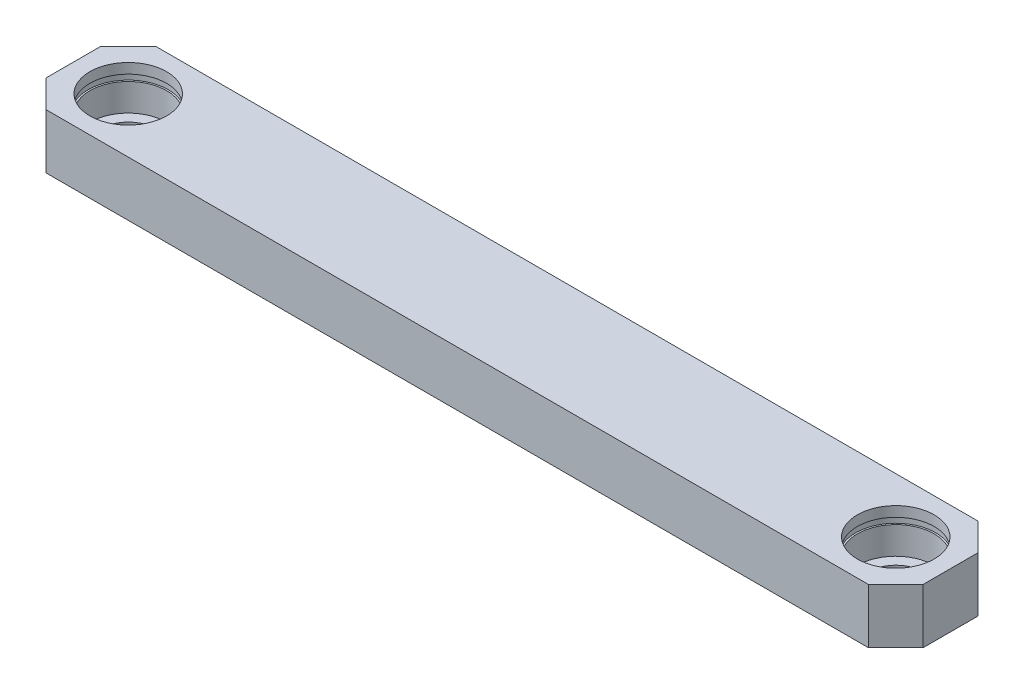
SolidWorks part; units mm, degrees
ref_plane "Front Plane" through (0, 0, 0) normal (0, 0, 1) x (1, 0, 0)
ref_plane "Top Plane" through (0, 0, 0) normal (0, 1, 0) x (1, 0, 0)
ref_plane "Right Plane" through (0, 0, 0) normal (1, 0, 0) x (0, 0, -1)
sketch "Sketch1" plane through (0, 0, 0) normal (0, 1, 0) x (1, 0, 0)
  line L0 (10, 10) -> (10, -10) construction
  line L1 (0, 10) -> (160, 10)
  line L2 (0, 10) -> (0, -10)
  line L3 (0, -10) -> (160, -10)
  line L4 (160, 10) -> (160, -10)
  line L5 (150, 10) -> (150, -10) construction
  dimension "L_s" = 160
  dimension "W" = 20
  dimension "F" = 10
  dimension "L" = 140
  dimension "MSM_11" = 10
extrude "Boss-Extrude1" add sketch "Sketch1" along normal blind 10
chamfer "Chamfer1" distance 5 angle 45 4 edges at (0, 5, -10) (160, 5, -10) (160, 5, 10) (0, 5, 10)
sketch "Sketch2" plane through (0, 0, 0) normal (0, 0, 1) x (1, 0, 0)
  line L0 (2.7, 7) -> (3, 7)
  line L1 (3, 7) -> (3, 2)
  line L2 (2.7, 8.15) -> (2.7, 7)
  line L3 (3, 2) -> (5, 2)
  line L4 (5, 2) -> (5, 0)
  line L5 (7.5, 10) -> (7.5, 0) construction
  line L6 (12.5, 10) -> (12.5, 0) construction
  line L7 (5, 0) -> (155, 0) construction
  line L8 (10, 10) -> (10, 0)
  line L9 (10, 0) -> (5, 0)
  line L10 (5, 10) -> (155, 10) construction
  line L11 (10, 10) -> (3, 10)
  line L12 (0, 10) -> (5, 10) construction
  line L13 (3, 10) -> (3, 8.15)
  line L14 (3, 8.15) -> (2.7, 8.15)
  line L15 (10, 10) -> (10, 0) construction
  line L16 (7.5, 10) -> (12.5, 10) construction
  line L17 (12.5, 0) -> (7.5, 0) construction
  dimension "D1" = 2
  dimension "D1._1" = 14
  dimension "DH_s_1" = 10
  dimension "MSM_1" = 14.6
  dimension "F" = 10
  dimension "B_1" = 5
  dimension "MSM_2" = 1.15
  dimension "D1_s" = 5
revolve "Cut-Revolve1" cut sketch "Sketch2" angle 360 about L15
hole_wizard "Diameter Hole1" [suppressed] positions "Sketch4" profile "Sketch3" hole size "Ø3.0" standard "JIS"
sketch "Sketch4" [suppressed] plane through (0, 10, 0) normal (0, 1, 0) x (1, 0, 0)
  line L0 (10, 10) -> (10, -10) construction
  line L1 (37, 10) -> (5, 10) construction
  line L2 (5, -10) -> (37, -10) construction
  point P0 (30, 0)
  dimension "L" = 140
  dimension "F" = 10
sketch "Sketch3" [suppressed] plane through (30, 10, 0) normal (1, 0, 0) x (0, 0, 1)
  line L0 (0, 0) -> (0, 10)
  line L1 (0, 10) -> (1.5, 10)
  line L2 (1.5, 10) -> (1.5, 0)
  line L5 (1.5, 0) -> (0, 0)
  line L11 (0, 0) -> (0, 10) construction
  dimension "E" = 3
  dimension "Thru Hole Depth" = 10
hole_wizard "Tapped Hole1" [suppressed] positions "Sketch6" profile "Sketch5" tap size "M3x0.5" standard "JIS"
sketch "Sketch6" [suppressed] plane through (0, 0, -10) normal (0, 0, -1) x (-1, 0, 0)
  line L0 (-10, 10) -> (-10, 0) construction
  line L1 (-37, 10) -> (-5, 10) construction
  line L2 (-37, 0) -> (-5, 0) construction
  point P0 (-30, 5)
  dimension "F" = 10
  dimension "L" = 140
  dimension "D1" = 5
sketch "Sketch5" [suppressed] plane through (30, 5, -10) normal (1, 0, 0) x (0, 1, 0)
  line L0 (0, 0) -> (0, 20)
  line L1 (0, 20) -> (1.25, 20)
  line L2 (1.25, 20) -> (1.25, 0)
  line L5 (1.25, 0) -> (0, 0)
  line L11 (0, 0) -> (0, 20) construction
  dimension "Thru Tap Drill Dia." = 2.5
  dimension "Thru Tap Drill Depth" = 20
cosmetic thread "Hole Thread1" [suppressed] parameters "M"=3
sketch "Sketch7" plane through (0, 0, 0) normal (0, 0, 1) x (1, 0, 0)
  line L0 (152.5, 0) -> (152.5, 10) construction
  line L1 (10, 10) -> (10, 0) construction
  line L2 (5, 10) -> (155, 10) construction
  line L3 (5, 0) -> (155, 0) construction
  line L4 (150, 10) -> (150, 0) construction
  line L5 (147.5, 10) -> (147.5, 0) construction
  line L6 (147.5, 0) -> (152.5, 0) construction
  line L7 (147.5, 10) -> (152.5, 10) construction
  line L8 (143, 10) -> (143, 8.15)
  line L9 (143, 8.15) -> (142.7, 8.15)
  line L10 (142.7, 8.15) -> (142.7, 7)
  line L11 (142.7, 7) -> (143, 7)
  line L12 (143, 7) -> (143, 2)
  line L13 (143, 2) -> (145, 2)
  line L14 (145, 2) -> (145, 0)
  line L15 (145, 0) -> (150, 0)
  line L16 (150, 10) -> (150, 0)
  line L17 (143, 10) -> (150, 10)
  dimension "D1" = 2
  dimension "F" = 10
  dimension "L" = 140
  dimension "D1._2" = 14
  dimension "MSM_6" = 14.6
  dimension "MSM_7" = 1.15
  dimension "B_2" = 5
  dimension "DH_s_2" = 10
  dimension "D2_s" = 5
revolve "Cut-Revolve2" cut sketch "Sketch7" angle 360 about L4
equation "\"D1@Sketch6\" = \"T@Boss-Extrude1\" / 2"
